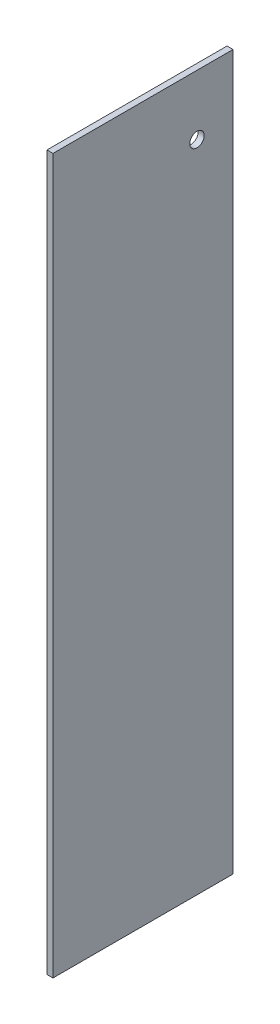
SolidWorks part; units mm, degrees
ref_plane "Front Plane" through (0, 0, 0) normal (0, 0, 1) x (1, 0, 0)
ref_plane "Top Plane" through (0, 0, 0) normal (0, 1, 0) x (1, 0, 0)
ref_plane "Right Plane" through (0, 0, 0) normal (1, 0, 0) x (0, 0, -1)
sketch "Sketch1" plane through (0, 0, 0) normal (0, 0, 1) x (1, 0, 0)
  line L0 (0, 0) -> (0, 381)
  line L5 (0, 381) -> (3.175, 381)
  line L6 (3.175, 381) -> (3.175, 3.175)
  line L7 (3.175, 3.175) -> (473.075, 3.175)
  line L8 (473.075, 3.175) -> (473.075, 0)
  line L9 (473.075, 0) -> (0, 0)
  dimension "D1" = 3.175
  dimension "D2" = 3.175
  dimension "D3" = 381
  dimension "D4" = 473.075
extrude "Boss-Extrude1" add sketch "Sketch1" along normal blind 95.25
sketch "Sketch2" plane through (0, 3.175, 0) normal (0, 1, 0) x (1, 0, 0)
  line L1 (473.075, -95.25) -> (3.175, -95.25) construction
  circle A0 centre (190.119, -4.572) radius 3.175
  circle A1 centre (190.119, -76.2) radius 3.175
  circle A2 centre (261.747, -4.572) radius 3.175
  circle A3 centre (261.747, -76.2) radius 3.175
  circle A4 centre (295.783, -76.2) radius 3.175
  circle A5 centre (295.783, -4.572) radius 3.175
  circle A6 centre (367.411, -76.2) radius 3.175
  circle A7 centre (367.411, -4.572) radius 3.175
  dimension "D3" = 6.35
  dimension "D1" = 6.35
  dimension "D2" = 19.05
  dimension "D4" = 71.628
  dimension "D5" = 71.628
  dimension "D6" = 71.628
  dimension "D7" = 6.35
  dimension "D8" = 6.35
extrude "Cut-Extrude1" cut sketch "Sketch2" against normal blind 152.4
sketch "Sketch4" plane through (0, 0, 0) normal (0, -1, 0) x (1, 0, 0)
  line L0 (473.075, 95.25) -> (473.075, 0) construction
  line L1 (0, 0) -> (473.075, 0) construction
  circle A0 centre (225.933, 40.386) radius 34.925
  circle A1 centre (331.597, 40.386) radius 34.925
  circle A2 centre (390.525, 19.05) radius 3.81
  dimension "D1" = 69.85
  dimension "D2" = 82.55
  dimension "D3" = 19.05
extrude "Cut-Extrude2" cut sketch "Sketch4" against normal blind 381
sketch "Sketch5" plane through (0, 0, 0) normal (-1, 0, 0) x (0, 0, 1)
  line L0 (95.25, 381) -> (0, 381) construction
  line L1 (0, 381) -> (0, 0) construction
  circle A0 centre (19.05, 349.25) radius 3.81
  dimension "D1" = 31.75
  dimension "D2" = 19.05
extrude "Cut-Extrude3" cut sketch "Sketch5" against normal blind 12.7
sketch "Sketch6" plane through (0, 0, 0) normal (0, -1, 0) x (1, 0, 0)
  line L1 (473.075, 95.25) -> (0, 95.25)
  line L2 (473.075, 95.25) -> (473.075, 0)
  line L3 (473.075, 0) -> (0, 0)
  line L4 (0, 95.25) -> (0, 0)
extrude "Cut-Extrude4" cut sketch "Sketch6" against normal up to surface (3.175 mm away) up to face at (260.858, 3.175, 40.386)
